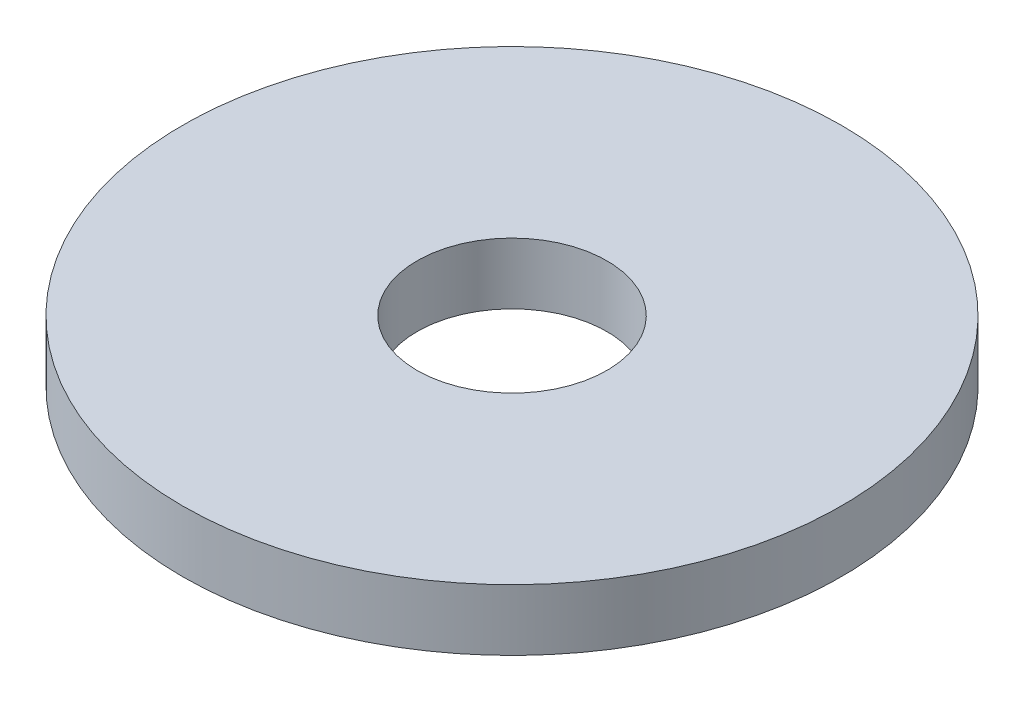
SolidWorks part; units mm, degrees
ref_plane "Front Plane" through (0, 0, 0) normal (0, 0, 1) x (1, 0, 0)
ref_plane "Top Plane" through (0, 0, 0) normal (0, 1, 0) x (1, 0, 0)
ref_plane "Right Plane" through (0, 0, 0) normal (1, 0, 0) x (0, 0, -1)
sketch "Sketch1" plane through (0, 0, 0) normal (0, 1, 0) x (1, 0, 0)
  circle A0 centre (0, 0) radius 31.23
  circle A1 centre (0, 0) radius 9
  dimension "D1" = 62.46
  dimension "D2" = 18
extrude "Boss-Extrude1" add sketch "Sketch1" along normal blind 5.81
ref_plane "Plane1" through (0, 2.905, 0) normal (0, 1, 0) x (1, 0, 0)
